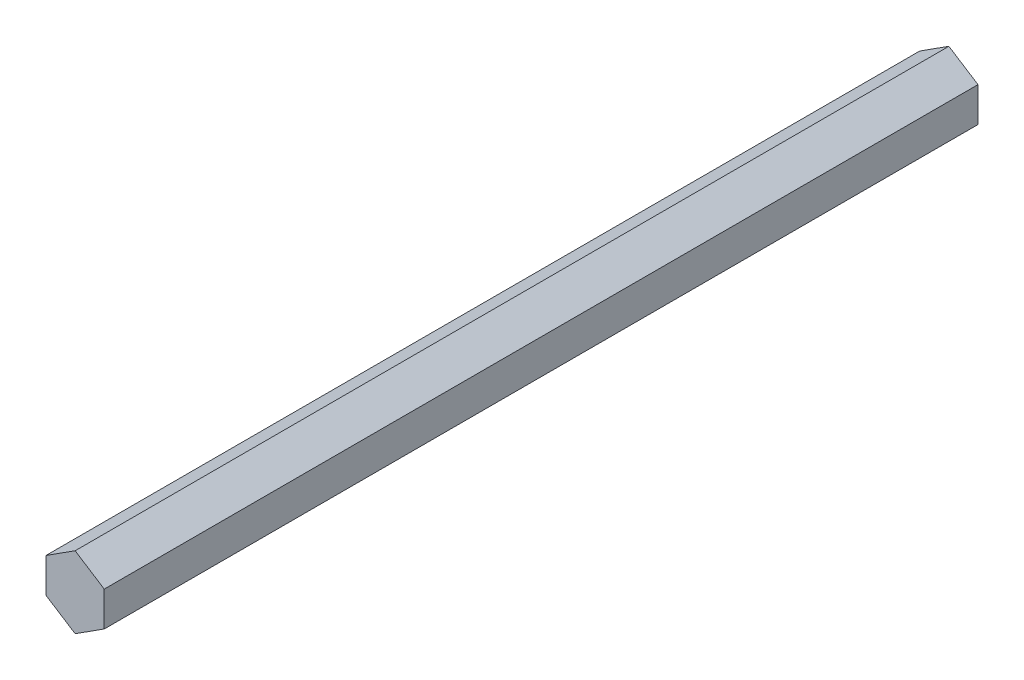
SolidWorks part; units mm, degrees
ref_plane "Front Plane" through (0, 0, 0) normal (1, 0, 0) x (0, 1, 0)
ref_plane "Top Plane" through (0, 0, 0) normal (0, 0, 1) x (0, 1, 0)
ref_plane "Right Plane" through (0, 0, 0) normal (0, 1, 0) x (-1, 0, 0)
sketch "Sketch1" plane through (0, 0, 0) normal (0, 0, 1) x (0, 1, 0)
  line L0 (0, 0) -> (4.523, 0)
  line L1 (4.523, 0) -> (6.9605, 3.81)
  line L2 (6.9605, 3.81) -> (4.523, 7.62)
  line L3 (4.523, 7.62) -> (0, 7.62)
  line L4 (0, 7.62) -> (-2.4375, 3.81)
  line L5 (-2.4375, 3.81) -> (0, 0)
  point P3 (2.6477, 0)
  point P8 (8.8901, 3.7024)
  point P9 (0, 0)
  dimension "D1" = 7.62
  dimension "D2" = 9.398
extrude "Boss-Extrude1" add sketch "Sketch1" along normal blind 114.3
